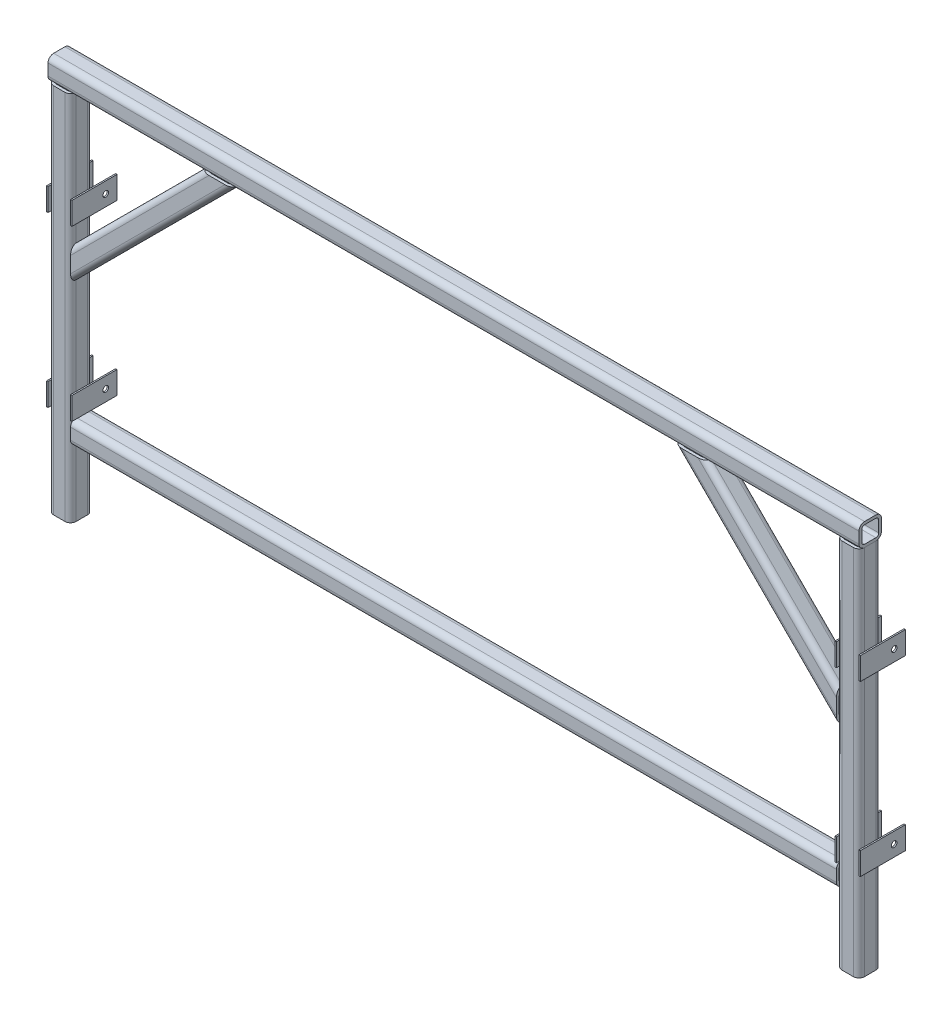
SolidWorks part; units mm, degrees
ref_plane "Front Plane" through (0, 0, 0) normal (0, 0, 1) x (1, 0, 0)
ref_plane "Top Plane" through (0, 0, 0) normal (0, 1, 0) x (1, 0, 0)
ref_plane "Right Plane" through (0, 0, 0) normal (1, 0, 0) x (0, 0, -1)
sketch "Sketch1" plane through (0, 0, 0) normal (0, 0, 1) x (1, 0, 0)
  line L0 (-889, -254) -> (889, -254)
  line L1 (-508, 431.8) -> (-889, 50.8)
  line L2 (-889, -431.8) -> (-889, 431.8)
  line L3 (-889, 431.8) -> (889, 431.8)
  line L4 (889, -431.8) -> (889, 431.8)
  line L5 (-889, -431.8) -> (889, 431.8) construction
  line L6 (-889, 431.8) -> (889, -431.8) construction
  line L7 (0, 0) -> (0, 431.8) construction
  line L8 (508, 431.8) -> (889, 50.8)
  point P0 (0, 0)
  dimension "D1" = 1778
  dimension "D2" = 863.6
  dimension "D3" = 177.8
  dimension "D4" = 381
  dimension "D5" = 381
other "Structural Member1"
ref_plane "Plane1" through (-889, 431.8, 0) normal (1, 0, 0) x (0, 1, 0)
sketch "Sketch11" plane through (-889, 431.8, 0) normal (1, 0, 0) x (0, 1, 0)
  line L0 (-12.7, -19.05) -> (12.7, -19.05)
  line L1 (-19.05, -12.7) -> (-19.05, 12.7)
  line L2 (12.7, 19.05) -> (-12.7, 19.05)
  line L3 (19.05, 12.7) -> (19.05, -12.7)
  line L4 (-12.7, -25.4) -> (12.7, -25.4)
  line L5 (-25.4, -12.7) -> (-25.4, 12.7)
  line L6 (12.7, 25.4) -> (-12.7, 25.4)
  line L7 (25.4, 12.7) -> (25.4, -12.7)
  line L8 (0, 0) -> (19.05, 0) construction
  line L9 (0, 0) -> (0, 19.05) construction
  arc A0 (25.4, 12.7) -> (12.7, 25.4) centre (12.7, 12.7) ccw
  arc A1 (12.7, -25.4) -> (25.4, -12.7) centre (12.7, -12.7) ccw
  arc A2 (-25.4, -12.7) -> (-12.7, -25.4) centre (-12.7, -12.7) ccw
  arc A3 (-12.7, 25.4) -> (-25.4, 12.7) centre (-12.7, 12.7) ccw
  arc A4 (-12.7, 19.05) -> (-19.05, 12.7) centre (-12.7, 12.7) ccw
  arc A5 (19.05, 12.7) -> (12.7, 19.05) centre (12.7, 12.7) ccw
  arc A6 (12.7, -19.05) -> (19.05, -12.7) centre (12.7, -12.7) ccw
  arc A7 (-19.05, -12.7) -> (-12.7, -19.05) centre (-12.7, -12.7) ccw
  point P3 (0, 25.4)
  point P4 (25.4, 0)
  point P5 (0, -25.4)
  point P6 (-25.4, 0)
  point P7 (-25.4, 25.4)
  point P8 (-25.4, -25.4)
  point P33 (0, 0)
  point P35 (25.4, -25.4)
  point P36 (25.4, 25.4)
  point P37 (0, 0)
  dimension "D1" = 12.7
  dimension "Thickness" = 6.35
  dimension "V_leg" = 50.8
other "Trim/Extend1"
other "Trim/Extend2"
sketch "Sketch12" plane through (914.4, 0, 0) normal (1, 0, 0) x (0, 0, -1)
  line L0 (-25.4, -431.8) -> (-25.4, 406.4) construction
  line L1 (-25.4, -228.6) -> (76.2, -228.6)
  line L2 (-25.4, -228.6) -> (-25.4, -177.8)
  line L3 (-25.4, -177.8) -> (76.2, -177.8)
  line L4 (76.2, -228.6) -> (76.2, -177.8)
  line L5 (76.2, -203.2) -> (-25.4, -203.2) construction
  line L6 (12.7, -431.8) -> (25.4, -431.8) construction
  line L7 (-25.4, -12.7) -> (25.4, -12.7) construction
  line L8 (25.4, -431.8) -> (25.4, 406.4) construction
  line L9 (-25.4, 203.2) -> (-25.4, 152.4)
  line L10 (-25.4, 152.4) -> (76.2, 152.4)
  line L11 (-25.4, 203.2) -> (76.2, 203.2)
  line L12 (76.2, 203.2) -> (76.2, 152.4)
  circle A0 centre (50.8, -203.2) radius 6.35
  circle A1 centre (50.8, 177.8) radius 6.35
  dimension "D5" = 12.7
  dimension "D1" = 50.8
  dimension "D2" = 101.6
  dimension "D3" = 228.6
  dimension "D4" = 25.4
extrude "Boss-Extrude1" add sketch "Sketch12" along normal blind 3.175 separate body
ref_plane "Plane2" through (889, 0, 0) normal (1, 0, 0) x (0, 0, -1)
mirror "Mirror1" about plane through (889, 0, 0) normal (1, 0, 0) of "Boss-Extrude1"
pattern_linear "LPattern2" count 2 spacing 1778 along (-1, 0, 0) of "Boss-Extrude1"
ref_plane "Plane4" through (-889, 0, 0) normal (1, 0, 0) x (0, 0, -1)
mirror "Mirror11" about plane through (-889, 0, 0) normal (1, 0, 0) of "LPattern2"
